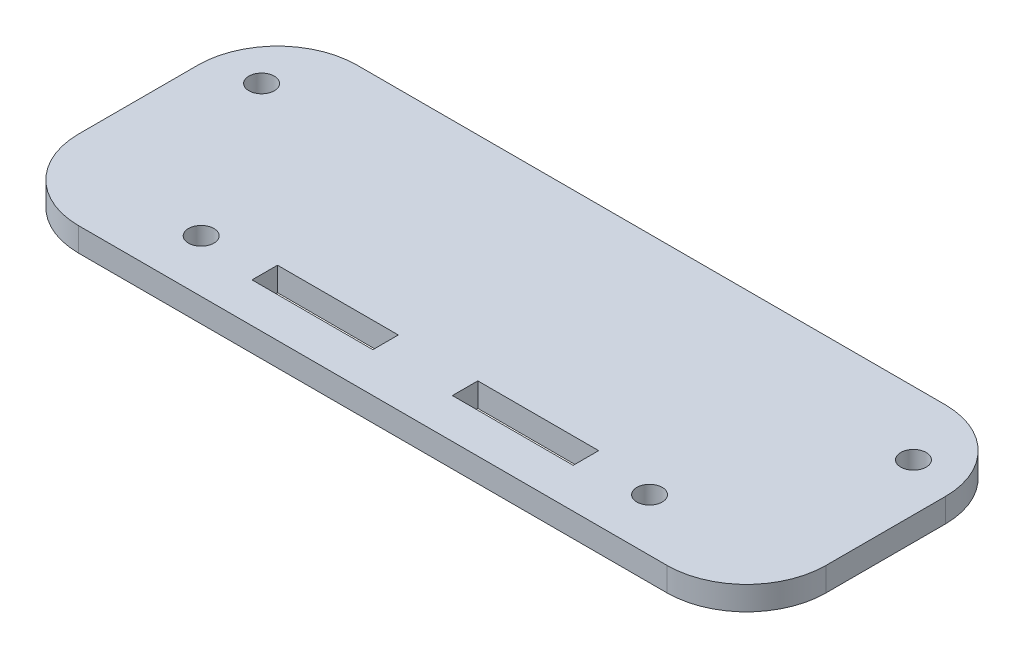
SolidWorks part; units mm, degrees
ref_plane "Front Plane" through (0, 0, 0) normal (0, 0, 1) x (1, 0, 0)
ref_plane "Top Plane" through (0, 0, 0) normal (0, 1, 0) x (1, 0, 0)
ref_plane "Right Plane" through (0, 0, 0) normal (1, 0, 0) x (0, 0, -1)
sketch "Sketch1" plane through (0, 0, 0) normal (0, 1, 0) x (1, 0, 0)
  line L0 (35, 109) -> (35, 0) construction
  line L1 (0, 0) -> (70, 0)
  line L2 (0, 0) -> (0, 109)
  line L3 (0, 109) -> (70, 109)
  line L4 (70, 0) -> (70, 109)
  line L5 (14.8, 8.2) -> (30, 8.2)
  line L6 (14.8, 8.2) -> (14.8, 5)
  line L7 (14.8, 5) -> (30, 5)
  line L8 (30, 8.2) -> (30, 5)
  line L9 (40, 8.2) -> (55.2, 8.2)
  line L10 (40, 8.2) -> (40, 5)
  line L11 (40, 5) -> (55.2, 5)
  line L12 (55.2, 8.2) -> (55.2, 5)
  line L13 (30, 6.6) -> (40, 6.6) construction
  line L14 (20, 54.5) -> (0, 54.5) construction
  circle A0 centre (6.8, 6.6) radius 1.6
  circle A1 centre (63.2, 6.6) radius 1.6
  circle A2 centre (6.8, 103) radius 1.6
  circle A3 centre (63.2, 103) radius 1.6
  point P17 (35, 6.6)
  dimension "D6" = 8
  dimension "D8" = 3.2
  dimension "D10" = 6
  dimension "D1" = 109
  dimension "D2" = 70
  dimension "D3" = 10
  dimension "D4" = 5
  dimension "D5" = 15.2
  dimension "D7" = 8
  dimension "D9" = 3.2
extrude "Boss-Extrude1" add sketch "Sketch1" along normal blind 3
sketch "Sketch3" plane through (0, 3, 0) normal (0, 1, 0) x (1, 0, 0)
  line L0 (70, 109) -> (0, 109) construction
  line L1 (0, 109) -> (70, 109)
  line L2 (0, 109) -> (0, 35)
  line L3 (0, 35) -> (70, 35)
  line L4 (70, 109) -> (70, 35)
  line L5 (70, 0) -> (70, 109) construction
  line L6 (63.2, 30) -> (63.2, 6.6)
  line L7 (0, 0) -> (70, 0) construction
  line L9 (6.8, 30) -> (6.8, 6.6)
  circle A0 centre (63.2, 30) radius 1.6
  circle A1 centre (6.8, 30) radius 1.6
  circle A2 centre (6.8, 6.6) radius 1.6 construction
  circle A3 centre (63.2, 6.6) radius 1.6 construction
  point P15 (0, 0)
  point P19 (0, 0)
  point P20 (63, 28.1036)
  point P23 (0, 0)
  point P24 (7.9384, 131.9235)
  point P25 (0, 0)
  line M13 (0, 109) -> (0, 0)
  line M15 (70, 0) -> (70, 109)
  line M16 (70, 109) -> (0, 109)
  circle M23 centre (63.2, 103) radius 1.6
  circle M24 centre (6.8, 103) radius 1.6
  dimension "D2" = 5
  dimension "D3" = 3.2
  dimension "D4" = 3.2
  dimension "D1" = 35
extrude "Cut-Extrude1" cut sketch "Sketch3" against normal through all contours L3 M13 M15 M16 M24 M23
sketch "Sketch4" plane through (0, 3, 0) normal (0, 1, 0) x (1, 0, 0)
  line L0 (70, 0) -> (70, 35) construction
  line L1 (70, 35) -> (82, 35)
  line L2 (70, 35) -> (70, 0)
  line L3 (70, 0) -> (82, 0)
  line L4 (82, 35) -> (82, 0)
  line L5 (0, 35) -> (70, 35) construction
  line L6 (0, 35) -> (0, 0) construction
  line L7 (0, 35) -> (-12, 35)
  line L8 (0, 35) -> (0, 0)
  line L9 (0, 0) -> (-12, 0)
  line L10 (-12, 35) -> (-12, 0)
  line L11 (0, 0) -> (70, 0) construction
  circle A0 centre (76, 27) radius 1.6
  circle A1 centre (-6, 27) radius 1.6
  point P18 (0, 0)
  point P19 (0, 0)
  point P20 (0, 0)
  point P21 (0, 0)
  point P22 (76, 0)
  point P23 (0, 0)
  point P24 (-6, 0)
  dimension "D2" = 8
  dimension "D3" = 3.2
  dimension "D1" = 12
extrude "Boss-Extrude2" add sketch "Sketch4" against normal up to surface (3 mm away) up to face at (35, 0, -17.5)
fillet "Fillet3" radius 10 4 edges at (-12, 1.5, 0) (-12, 1.5, -35) (82, 1.5, 0) (82, 1.5, -35)
